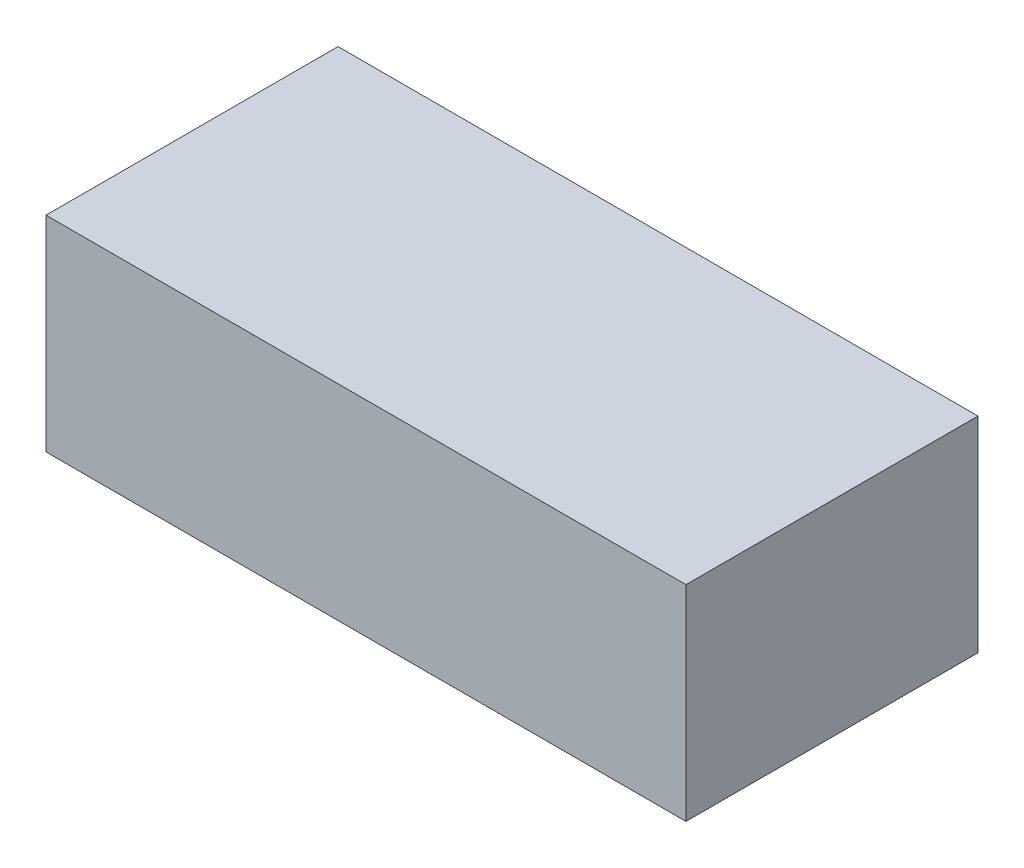
SolidWorks part; units mm, degrees
material "Ba tLeão 6s 5200mah"
ref_plane "Plano frontal" through (0, 0, 0) normal (0, 0, 1) x (1, 0, 0)
ref_plane "Plano superior" through (0, 0, 0) normal (0, 1, 0) x (1, 0, 0)
ref_plane "Plano direito" through (0, 0, 0) normal (1, 0, 0) x (0, 0, -1)
sketch "Esboço1" plane through (0, 0, 0) normal (0, 0, 1) x (1, 0, 0)
  line L1 (-51.5, 16.5) -> (51.5, 16.5)
  line L2 (-51.5, 16.5) -> (-51.5, -16.5)
  line L3 (-51.5, -16.5) -> (51.5, -16.5)
  line L4 (51.5, 16.5) -> (51.5, -16.5)
  line L5 (-51.5, 16.5) -> (51.5, -16.5) construction
  line L6 (-51.5, -16.5) -> (51.5, 16.5) construction
  point P0 (0, 0)
  dimension "D1" = 103
  dimension "D2" = 33
extrude "Ressalto-extrusão1" add sketch "Esboço1" along normal mid plane 47
